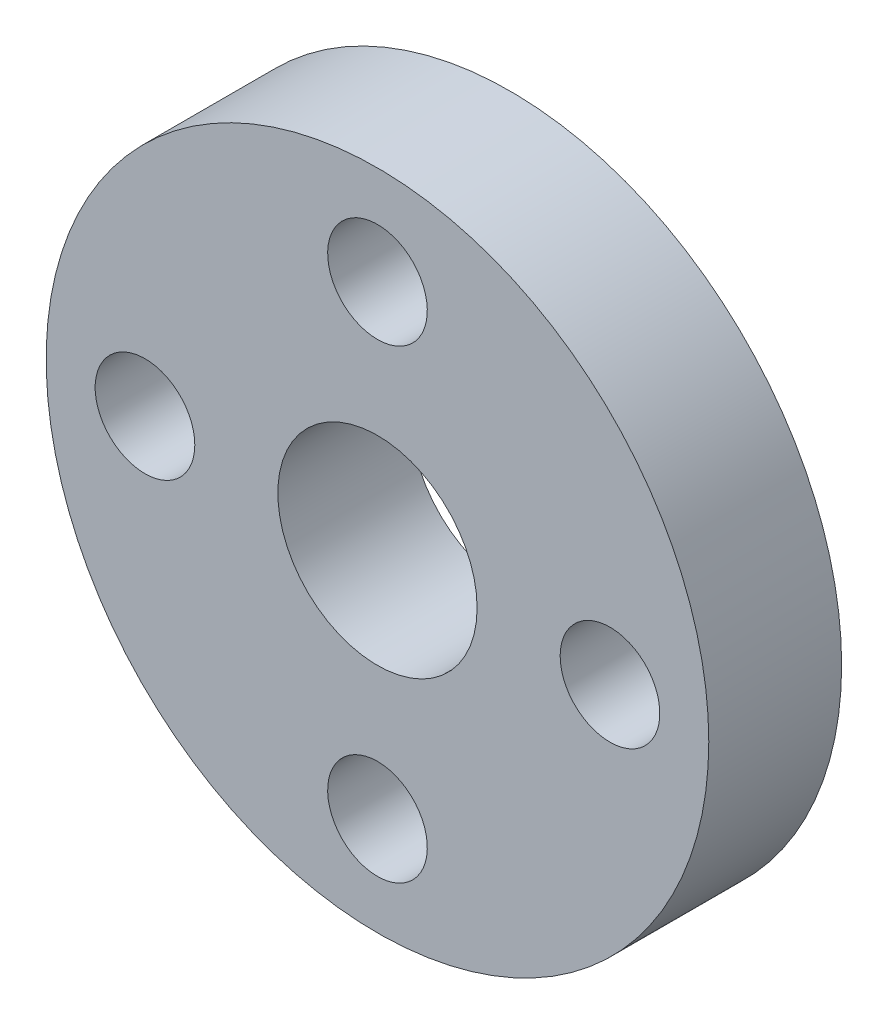
SolidWorks part; units mm, degrees
ref_plane "前视基准面" through (0, 0, 0) normal (0, 0, 1) x (1, 0, 0)
ref_plane "上视基准面" through (0, 0, 0) normal (0, 1, 0) x (1, 0, 0)
ref_plane "右视基准面" through (0, 0, 0) normal (1, 0, 0) x (0, 0, -1)
sketch "草图1" plane through (0, 0, 0) normal (0, 0, 1) x (1, 0, 0)
  circle A0 centre (0, 0) radius 9.975
extrude "凸台-拉伸1" add sketch "草图1" along normal blind 4
sketch "草图2" plane through (0, 0, 4) normal (0, 0, 1) x (1, 0, 0)
  circle A0 centre (0, 0) radius 7 construction
  circle A1 centre (-7, 0) radius 1.5
extrude "切除-拉伸1" cut sketch "草图2" against normal through all
pattern_circular "阵列(圆周)1" count 4 over 360 about axis through (0, 0, 0) along (0, 0, 1) of "切除-拉伸1"
sketch "草图3" plane through (0, 0, 4) normal (0, 0, 1) x (1, 0, 0)
  circle A0 centre (0, 0) radius 3
extrude "切除-拉伸2" cut sketch "草图3" against normal through all
